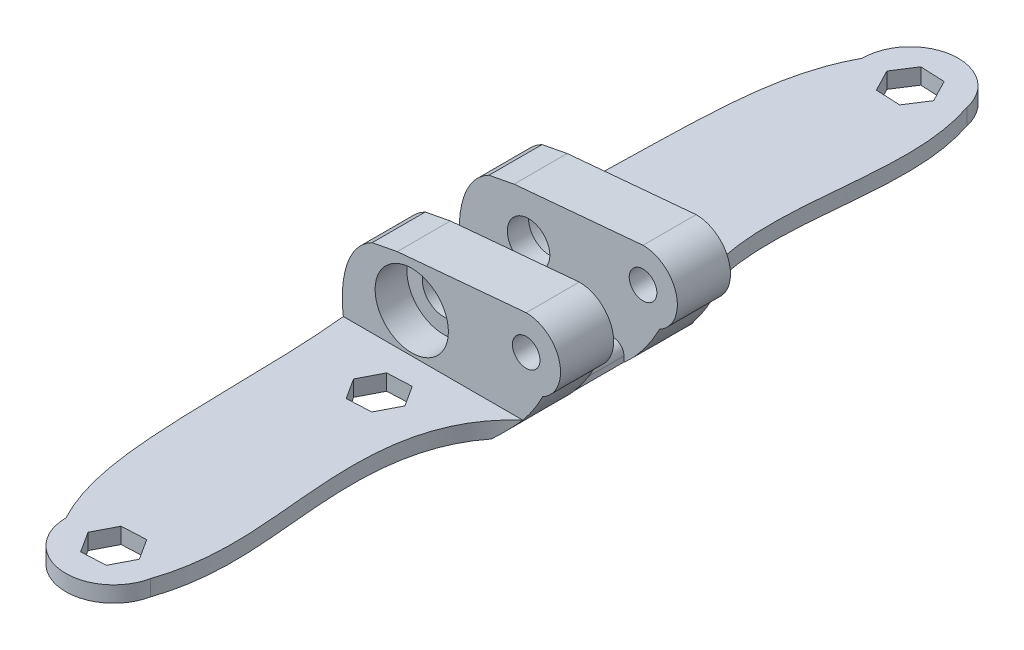
SolidWorks part; units mm, degrees
ref_plane "Front Plane" through (0, 0, 0) normal (0, 0, 1) x (1, 0, 0)
ref_plane "Top Plane" through (0, 0, 0) normal (0, 1, 0) x (1, 0, 0)
ref_plane "Right Plane" through (0, 0, 0) normal (1, 0, 0) x (0, 0, -1)
sketch "Sketch1" plane through (0, 0, 0) normal (0, 0, 1) x (1, 0, 0)
  line L0 (-139.182, -34.0354) -> (-124.7357, -34.0354)
  line L5 (-155.0708, -34.0354) -> (-139.182, -34.0354)
  line L6 (-121.2243, -13.1941) -> (-145.5043, -15.3702)
  arc A0 (-118.1107, -25.3371) -> (-122.3749, -13.2972) centre (-121.2243, -19.6648) ccw
  circle A1 centre (-121.2243, -19.6648) radius 2.6
  circle A2 centre (-142.7777, -23.6192) radius 6.9
  spline S0 degree 2 poles (-124.7357, -34.0354) (-120.8681, -30.6349) (-118.1107, -25.3371) knots 0.604914 0.604914 0.604914 1 1 1
  spline S1 degree 2 poles (-145.5043, -15.3702) (-147.6654, -15.752) (-150.2379, -16.2788) knots 0 0 0 0.143499 0.143499 0.143499
  spline S2 degree 3 poles (-150.2379, -16.2788) (-156.3314, -19.4124) (-156.5873, -28.5049) (-155.0708, -34.0354) knots 0 0 0 0 1 1 1 1
extrude "Boss-Extrude1" add sketch "Sketch1" along normal blind 10
sketch "Sketch2" plane through (0, 0, 0) normal (0, 0, -1) x (-1, 0, 0)
  line L1 (155.0708, -34.0354) -> (124.7357, -34.0354) construction
  line L2 (124.8108, -34.0354) -> (124.8108, -33.0354)
  line L3 (126.8108, -31.0354) -> (155.6602, -31.0354)
  line L4 (124.8108, -34.0354) -> (155.0708, -34.0354)
  arc A0 (124.8108, -33.0354) -> (126.8108, -31.0354) centre (126.8108, -33.0354) cw
  spline S1 degree 2 poles (155.6602, -31.0354) (155.4533, -32.2208) (155.0708, -34.0354) knots 0.46928 0.46928 0.46928 1.113861 1.113861 1.113861
  spline S2 degree 3 poles (150.2379, -16.2788) (156.3314, -19.4124) (156.5873, -28.5049) (155.0708, -34.0354) knots 0 0 0 0 1 1 1 1 construction
  dimension "D2" = 2
  dimension "D1" = 3
extrude "Boss-Extrude2" add sketch "Sketch2" along normal blind 12
ref_plane "Plane1" through (0, 0, -6) normal (0, 0, -1) x (-1, 0, 0)
mirror "Mirror1" about plane through (0, 0, -6) normal (0, 0, -1) of "Boss-Extrude1"
sketch "Sketch3" plane through (0, 0, 0) normal (0, 0, -1) x (-1, 0, 0)
  circle A0 centre (142.7777, -23.6192) radius 4
  circle A1 centre (142.7777, -23.6192) radius 7
  dimension "D1" = 8
  dimension "D2" = 14
extrude "Boss-Extrude3" add sketch "Sketch3" against normal blind 4
mirror "Mirror2" about plane through (0, 0, -6) normal (0, 0, -1) of "Boss-Extrude3"
sketch "Sketch4" plane through (0, 0, 10) normal (0, 0, 1) x (1, 0, 0)
  line L3 (-155.0708, -34.0354) -> (-124.7357, -34.0354) construction
  line L4 (-155.0708, -34.0354) -> (-124.7357, -34.0354)
  line L5 (-155.6602, -31.0354) -> (-121.839, -31.0354)
  parabola Q0 (-124.7357, -34.0354) -> (-118.1107, -25.3371) focus (-134.2829, -26.659) apex (-128.4106, -36.6937) construction
  parabola Q1 (-124.7357, -34.0354) -> (-121.839, -31.0354) focus (-134.2829, -26.659) apex (-128.4106, -36.6937)
  spline S3 degree 3 poles (1418.4323, -2568.4115) (-1494.8779, 2800.3488) (936.9377, -2971.3238) (-991.0388, 2845.1787) knots -5.924969 -5.924969 -5.924969 -5.924969 7.440007 7.440007 7.440007 7.440007 only from (-150.2379, -16.2788) to (-155.0708, -34.0354) construction
  spline S4 degree 3 poles (-155.6602, -31.0354) (-155.5248, -32.1044) (-155.3221, -33.1188) (-155.0708, -34.0354) knots 0.834264 0.834264 0.834264 0.834264 1 1 1 1
  line M7 (-155.0708, -34.0354) -> (-124.7357, -34.0354)
  spline M9 degree 2 poles (-124.7357, -34.0354) (-120.8681, -30.6349) (-118.1107, -25.3371) knots 0.604914 0.604914 0.604914 1 1 1
  spline M15 degree 3 poles (-150.2379, -16.2788) (-156.3314, -19.4124) (-156.5873, -28.5049) (-155.0708, -34.0354) knots 0 0 0 0 1 1 1 1
  dimension "D1" = 3
extrude "Boss-Extrude4" add sketch "Sketch4" along normal blind 84 contours L5 M15 M7 M9
sketch "Sketch5" plane through (0, 0, -22) normal (0, 0, -1) x (-1, 0, 0)
  line L4 (155.0708, -34.0354) -> (124.7357, -34.0354) construction
  line L12 (155.6602, -31.0354) -> (121.839, -31.0354) construction
  line L13 (155.0708, -34.0354) -> (124.7357, -34.0354)
  line L14 (155.6602, -31.0354) -> (121.839, -31.0354)
  parabola Q1 (124.7357, -34.0354) -> (121.839, -31.0354) focus (134.2829, -26.659) apex (128.4106, -36.6937) construction
  parabola Q2 (124.7357, -34.0354) -> (121.839, -31.0354) focus (134.2829, -26.659) apex (128.4106, -36.6937)
  spline S0 degree 3 poles (-940.0385, -1700.278) (1070.9853, 1882.8118) (-569.2522, -2026.0721) (681.2923, 1894.3267) knots -5.104421 -5.104421 -5.104421 -5.104421 6.614169 6.614169 6.614169 6.614169 only from (155.6602, -31.0354) to (155.0708, -34.0354) construction
  spline S1 degree 3 poles (155.6602, -31.0354) (155.5248, -32.1044) (155.3221, -33.1188) (155.0708, -34.0354) knots 0.834264 0.834264 0.834264 0.834264 1 1 1 1
extrude "Boss-Extrude5" add sketch "Sketch5" along normal blind 84
ref_plane "Plane2" through (0, 0, -6) normal (0, 0, 1) x (1, 0, 0)
sketch "Sketch6" plane through (0, -31.0354, 0) normal (0, 1, 0) x (1, 0, 0)
  line L0 (-137.7864, 76.8948) -> (-142.4, 77.1142)
  line L1 (-142.4, 77.1142) -> (-144.5168, 81.2194)
  line L2 (-144.5168, 81.2194) -> (-142.0201, 85.1052)
  line L3 (-142.0201, 85.1052) -> (-137.4065, 84.8858)
  line L4 (-137.4065, 84.8858) -> (-135.2897, 80.7806)
  line L5 (-135.2897, 80.7806) -> (-137.7864, 76.8948)
  line L6 (-135.2897, 30.7806) -> (-137.7864, 26.8948)
  line L7 (-144.5168, 31.2194) -> (-142.0201, 35.1052)
  line L8 (-137.7864, 26.8948) -> (-142.4, 27.1142)
  line L9 (-137.4065, 34.8858) -> (-135.2897, 30.7806)
  line L10 (-142.4, 27.1142) -> (-144.5168, 31.2194)
  line L11 (-142.0201, 35.1052) -> (-137.4065, 34.8858)
  line L24 (-155.6602, 22) -> (-173.4653, 22)
  line L25 (-173.4653, 22) -> (-173.4653, 117.8341)
  line L26 (-173.4653, 117.8341) -> (-100.4309, 117.8341)
  line L27 (-100.4309, 117.8341) -> (-121.839, 22)
  line L28 (-252.8971, 6) -> (-193.8751, 6) construction
  line L29 (-100.4309, -105.8341) -> (-121.839, -10)
  line L30 (-173.4653, -105.8341) -> (-100.4309, -105.8341)
  line L31 (-173.4653, -10) -> (-173.4653, -105.8341)
  line L32 (-155.6602, -10) -> (-173.4653, -10)
  line L33 (-142.0201, -23.1052) -> (-137.4065, -22.8858)
  line L34 (-142.4, -15.1142) -> (-144.5168, -19.2194)
  line L35 (-137.4065, -22.8858) -> (-135.2897, -18.7806)
  line L36 (-137.7864, -14.8948) -> (-142.4, -15.1142)
  line L37 (-144.5168, -19.2194) -> (-142.0201, -23.1052)
  line L38 (-135.2897, -18.7806) -> (-137.7864, -14.8948)
  line L39 (-135.2897, -68.7806) -> (-137.7864, -64.8948)
  line L40 (-137.4065, -72.8858) -> (-135.2897, -68.7806)
  line L41 (-142.0201, -73.1052) -> (-137.4065, -72.8858)
  line L42 (-144.5168, -69.2194) -> (-142.0201, -73.1052)
  line L43 (-142.4, -65.1142) -> (-144.5168, -69.2194)
  line L44 (-137.7864, -64.8948) -> (-142.4, -65.1142)
  arc A0 (-131.072, 82.8635) -> (-148.929, 81) centre (-139.9032, 81) ccw
  arc A1 (-131.072, -70.8635) -> (-148.929, -69) centre (-139.9032, -69) cw
  spline S0 degree 3 poles (-121.839, 22) (-130.238, 29.2882) (-131.7087, 51.8195) (-127.4759, 72.231) (-131.072, 82.8635) knots 0 0 0 0 0.490729 1 1 1 1
  spline S1 degree 3 poles (-148.929, 81) (-152.6254, 74.0818) (-155.2624, 54.1051) (-154.4029, 34.2446) (-155.6602, 22) knots 0 0 0 0 0.385425 1 1 1 1
  spline S2 degree 3 poles (-148.929, -69) (-152.6254, -62.0818) (-155.2624, -42.1051) (-154.4029, -22.2446) (-155.6602, -10) knots 0 0 0 0 0.385425 1 1 1 1
  spline S3 degree 3 poles (-121.839, -10) (-130.238, -17.2882) (-131.7087, -39.8195) (-127.4759, -60.231) (-131.072, -70.8635) knots 0 0 0 0 0.490729 1 1 1 1
extrude "Cut-Extrude1" cut sketch "Sketch6" against normal through all
